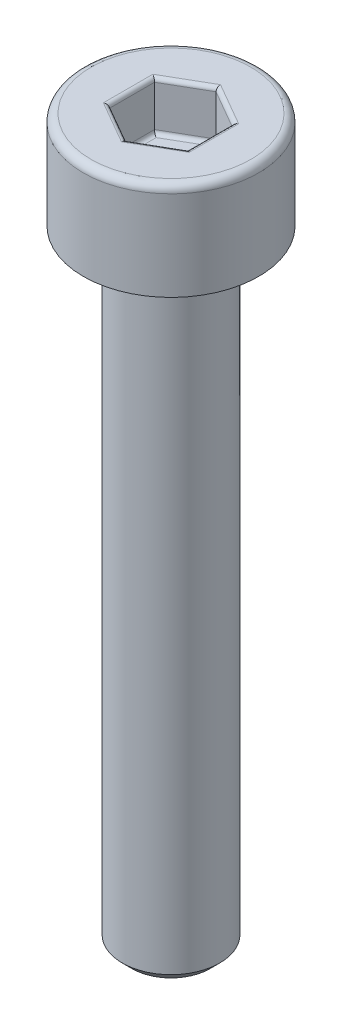
SolidWorks part; units mm, degrees
ref_plane "Front Plane" through (0, 0, 0) normal (0, 0, 1) x (1, 0, 0)
ref_plane "Top Plane" through (0, 0, 0) normal (0, 1, 0) x (1, 0, 0)
ref_plane "Right Plane" through (0, 0, 0) normal (1, 0, 0) x (0, 0, -1)
sketch "Sketch1" plane through (0, 0, 0) normal (0, 0, 1) x (1, 0, 0)
  line L0 (0, 0) -> (0, -47.0967) construction
  line L1 (0, -18.5) -> (-1.25, -18.5)
  line L2 (-1.25, -18.5) -> (-1.25, -2.5)
  line L3 (-1.25, -2.5) -> (-2.25, -2.5)
  line L4 (-2.25, -2.5) -> (-2.25, 0)
  line L5 (-2.25, 0) -> (0, 0)
  line L6 (0, 0) -> (0, -18.5)
  dimension "d" = 2.5
  dimension "l" = 18.5
  dimension "k" = 2.5
  dimension "dk" = 4.5
revolve "Revolve1" add sketch "Sketch1" angle 360 about L0
chamfer "Chamfer1" distance 0.25 angle 45 2 edges at (0, -2.5, 1.25) (0, -18.5, 1.25)
fillet "Fillet1" radius 0.2 1 edges at (0, 0, 2.25)
sketch "Sketch2" plane through (0, 0, 0) normal (0, 1, 0) x (1, 0, 0)
  line L1 (0, 1.1547) -> (-1, 0.5774)
  line L2 (-1, 0.5774) -> (-1, -0.5774)
  line L3 (-1, -0.5774) -> (0, -1.1547)
  line L4 (0, -1.1547) -> (1, -0.5774)
  line L5 (1, -0.5774) -> (1, 0.5774)
  line L6 (1, 0.5774) -> (0, 1.1547)
  circle A0 centre (0, 0) radius 1 construction
  dimension "s" = 2
extrude "Cut-Extrude1" cut sketch "Sketch2" against normal blind 1.25
fillet "Fillet2" radius 0.1 12 edges at (-0.5, 0, -0.866) (-1, 0, 0) (-0.5, 0, 0.866) (0.5, 0, 0.866) (1, 0, 0) (0.5, 0, -0.866) (1, -1.25, 0) (0.5, -1.25, 0.866) (-0.5, -1.25, 0.866) (-1, -1.25, 0) (-0.5, -1.25, -0.866) (0.5, -1.25, -0.866)
